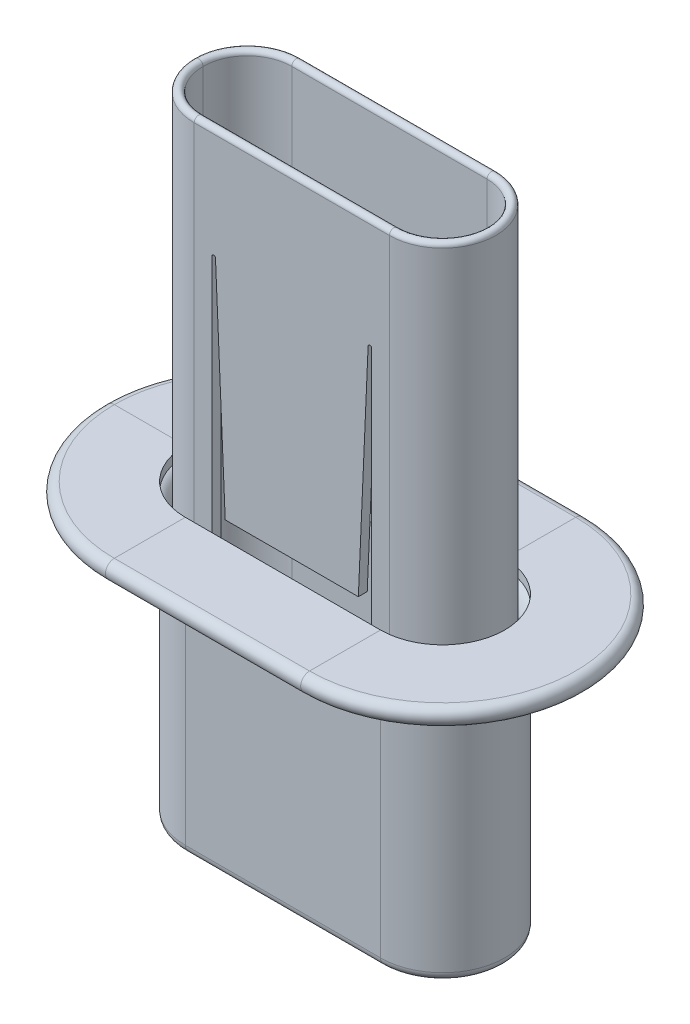
SolidWorks part; units mm, degrees
ref_plane "Front Plane" through (0, 0, 0) normal (0, 0, 1) x (1, 0, 0)
ref_plane "Top Plane" through (0, 0, 0) normal (0, 1, 0) x (1, 0, 0)
ref_plane "Right Plane" through (0, 0, 0) normal (1, 0, 0) x (0, 0, -1)
sketch "Sketch1" plane through (0, 0, 0) normal (0, 0, 1) x (1, 0, 0)
  line L0 (-1.6, 4.05) -> (-1.6, -2.95)
  line L1 (-1.8, -2.95) -> (-1.8, 0)
  line L2 (-1.85, 0.05) -> (-2.6, 0.05)
  line L3 (-2.6, 0.25) -> (-1.8, 0.25)
  line L4 (-1.8, 0.25) -> (-1.8, 0.15)
  line L5 (-1.8, 0.15) -> (-1.85, 0.15)
  line L6 (-1.7, 0) -> (-1.7, 4.05)
  line L7 (-1.7, 0) -> (-1.6, 0) construction
  arc A0 (-1.6, -2.95) -> (-1.8, -2.95) centre (-1.7, -2.95) cw
  arc A1 (-1.8, 0) -> (-1.85, 0.05) centre (-1.85, 0) ccw
  arc A2 (-2.6, 0.05) -> (-2.6, 0.25) centre (-2.6, 0.15) cw
  arc A3 (-1.85, 0.15) -> (-1.7, 0) centre (-1.85, 0) cw
  arc A4 (-1.7, 4.05) -> (-1.6, 4.05) centre (-1.65, 4.05) cw
  point P17 (0, 0)
  point P18 (-2.5993, 1.0153)
  point P19 (-5.1096, 0.6662)
  point P20 (-1.85, 0.15)
  point P23 (0, 0)
  dimension "D6" = 0.05
  dimension "D1" = 0.1
  dimension "D2" = 1
  dimension "D3" = 4
  dimension "D4" = 3
  dimension "D5" = 1.6
sketch "Sketch2" plane through (0, 0, 0) normal (0, 1, 0) x (1, 0, 0)
  line L0 (-1.1, 0) -> (1.1, 0) construction
  line L1 (-1.1, 0.5) -> (1.1, 0.5)
  line L2 (-1.1, -0.5) -> (1.1, -0.5)
  line L3 (-1.7, 0) -> (-1.6, 0) construction
  arc A0 (-1.1, 0.5) -> (-1.1, -0.5) centre (-1.1, 0) ccw
  arc A1 (1.1, -0.5) -> (1.1, 0.5) centre (1.1, 0) ccw
  point P3 (0, 0)
  point P8 (0, 0)
  dimension "D1" = 1
sweep "Sweep1" add profiles "Sketch1" path "Sketch2"
sketch "Sketch6" plane through (0, 0, -0.6) normal (0, 0, -1) x (-1, 0, 0)
  line L0 (-0.9, 2.85) -> (-0.86, 2.85) construction
  line L1 (-0.86, 2.85) -> (-0.75, 0.35)
  line L2 (-0.75, 0.35) -> (0.75, 0.35)
  line L3 (0.75, 0.35) -> (0.86, 2.85)
  line L4 (0.86, 2.85) -> (0.9, 2.85) construction
  line L5 (0.9, 2.85) -> (0.9, 0.05)
  line L6 (0.9, 0.05) -> (-0.9, 0.05)
  line L7 (-0.9, 0.05) -> (-0.9, 2.85)
  line L8 (1.1, 0.05) -> (-1.1, 0.05) construction
  arc A0 (-0.9, 2.85) -> (-0.86, 2.85) centre (-0.88, 2.85) cw
  arc A1 (0.86, 2.85) -> (0.9, 2.85) centre (0.88, 2.85) cw
  point P8 (0, 0.05)
  point P9 (0, 0.35)
  point P12 (0.88, 2.85)
  dimension "D5" = 0.02
  dimension "D1" = 2.8
  dimension "D2" = 2.5
  dimension "D3" = 1.8
  dimension "D4" = 1.5
extrude "Cut-Extrude1" cut sketch "Sketch6" against normal up to surface (1.2 mm away) up to face at (0, 2.025, 0.6)
